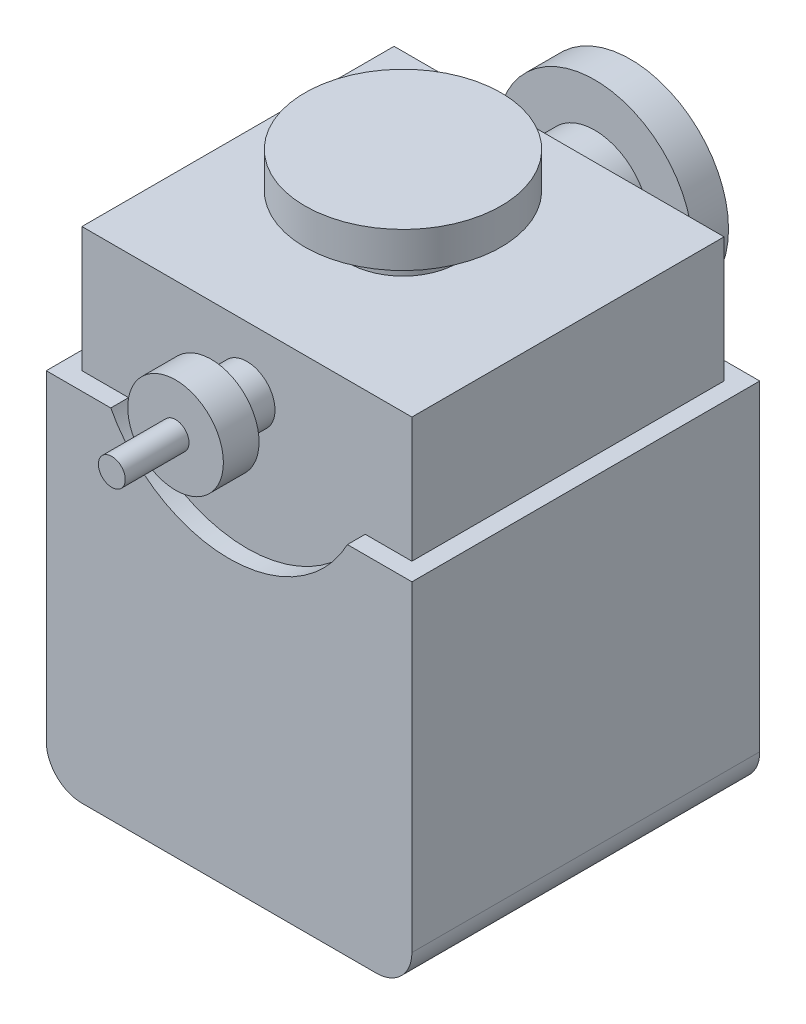
SolidWorks part; units mm, degrees
ref_plane "Front Plane" through (0, 0, 0) normal (0, 0, 1) x (1, 0, 0)
ref_plane "Top Plane" through (0, 0, 0) normal (0, 1, 0) x (1, 0, 0)
ref_plane "Right Plane" through (0, 0, 0) normal (1, 0, 0) x (0, 0, -1)
sketch "Sketch1" plane through (0, 0, 0) normal (0, 1, 0) x (1, 0, 0)
  circle A0 centre (0, 0) radius 34.925
  dimension "D1" = 69.85
extrude "Boss-Extrude1" add sketch "Sketch1" along normal blind 12.69
sketch "Sketch2" plane through (0, 0, 0) normal (0, -1, 0) x (-1, 0, 0)
  circle A0 centre (0, 0) radius 19.4
  dimension "D1" = 38.8
extrude "Boss-Extrude2" add sketch "Sketch2" along normal blind 12.69
sketch "Sketch7" plane through (0, -12.69, 0) normal (0, -1, 0) x (1, 0, 0)
  line L1 (-58.7375, -55.5625) -> (58.7375, -55.5625)
  line L2 (-58.7375, -55.5625) -> (-58.7375, 55.5625)
  line L3 (-58.7375, 55.5625) -> (58.7375, 55.5625)
  line L4 (58.7375, -55.5625) -> (58.7375, 55.5625)
  line L5 (-58.7375, -55.5625) -> (58.7375, 55.5625) construction
  line L6 (-58.7375, 55.5625) -> (58.7375, -55.5625) construction
  point P0 (0, 0)
  dimension "D1" = 111.125
  dimension "D2" = 117.475
extrude "Boss-Extrude3" add sketch "Sketch7" along normal blind 44.45
sketch "Sketch8" plane through (0, -57.14, 0) normal (0, -1, 0) x (1, 0, 0)
  line L1 (-65.0875, 61.9125) -> (65.0875, 61.9125)
  line L2 (-65.0875, 61.9125) -> (-65.0875, -61.9125)
  line L3 (-65.0875, -61.9125) -> (65.0875, -61.9125)
  line L4 (65.0875, 61.9125) -> (65.0875, -61.9125)
  line L5 (-65.0875, 61.9125) -> (65.0875, -61.9125) construction
  line L6 (-65.0875, -61.9125) -> (65.0875, 61.9125) construction
  point P0 (0, 0)
  dimension "D1" = 123.825
  dimension "D2" = 130.175
extrude "Boss-Extrude4" add sketch "Sketch8" along normal blind 127
fillet "Fillet1" radius 12.7 1 edges at (65.0875, -184.14, 0)
fillet "Fillet2" radius 12.7 1 edges at (-65.0875, -184.14, 0)
sketch "Sketch9" plane through (0, 0, -55.5625) normal (0, 0, -1) x (-1, 0, 0)
  line L0 (0, -12.69) -> (0, -57.14) construction
  line L1 (58.7375, -12.69) -> (-58.7375, -12.69) construction
  line L2 (65.0875, -57.14) -> (-65.0875, -57.14) construction
  circle A0 centre (0, -34.915) radius 47.625
  dimension "D1" = 95.25
extrude "Cut-Extrude1" cut sketch "Sketch9" along normal through all contours A0
sketch "Sketch10" plane through (0, 0, -55.5625) normal (0, 0, -1) x (-1, 0, 0)
  circle A0 centre (0, -34.915) radius 19.4
extrude "Boss-Extrude5" add sketch "Sketch10" along normal blind 12.7
sketch "Sketch11" plane through (0, 0, -68.2625) normal (0, 0, -1) x (-1, 0, 0)
  circle A0 centre (0, -34.915) radius 34.925
extrude "Boss-Extrude6" add sketch "Sketch11" along normal blind 12.7
sketch "Sketch17" plane through (0, 0, 55.5625) normal (0, 0, 1) x (1, 0, 0)
  circle A0 centre (0, -34.915) radius 47.625
  dimension "D1" = 95.25
extrude "Cut-Extrude3" cut sketch "Sketch17" along normal through all contours A0
sketch "Sketch13" plane through (0, 0, 55.5625) normal (0, 0, 1) x (1, 0, 0)
  circle A0 centre (0, -34.915) radius 10
  dimension "D1" = 20
extrude "Boss-Extrude7" add sketch "Sketch13" along normal blind 12.7
sketch "Sketch14" plane through (0, 0, 68.2625) normal (0, 0, 1) x (1, 0, 0)
  circle A0 centre (0, -34.915) radius 17.018
extrude "Boss-Extrude8" add sketch "Sketch14" along normal blind 12.7
sketch "Sketch15" plane through (0, 0, 80.9625) normal (0, 0, 1) x (1, 0, 0)
  circle A0 centre (0, -34.915) radius 4.7856
extrude "Boss-Extrude9" add sketch "Sketch15" along normal blind 22.7
